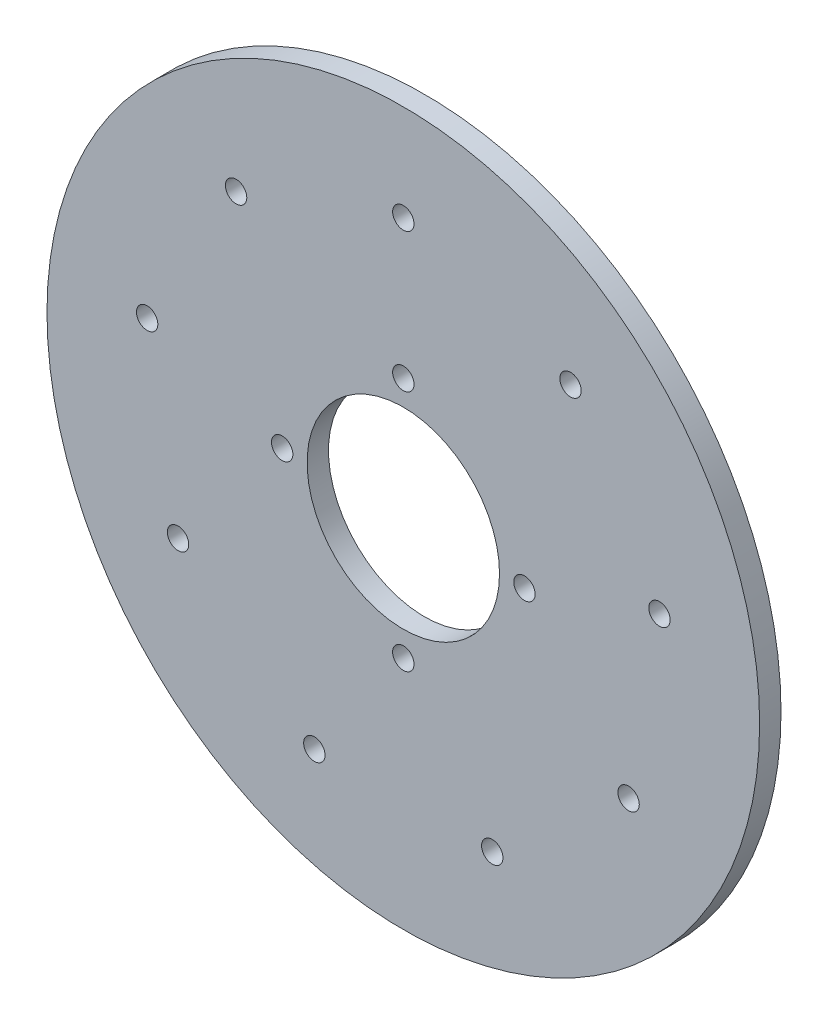
SolidWorks part; units mm, degrees
ref_plane "前视基准面" through (0, 0, 0) normal (0, 0, 1) x (1, 0, 0)
ref_plane "上视基准面" through (0, 0, 0) normal (0, 1, 0) x (1, 0, 0)
ref_plane "右视基准面" through (0, 0, 0) normal (1, 0, 0) x (0, 0, -1)
sketch "草图1" plane through (0, 0, 0) normal (0, 0, 1) x (1, 0, 0)
  line L0 (0, 0) -> (0, 17) construction
  line L1 (0, 0) -> (0, 36.5) construction
  circle A0 centre (0, 0) radius 50
  circle A1 centre (0, 17) radius 1.5
  circle A2 centre (17, 0) radius 1.5
  circle A3 centre (0, -17) radius 1.5
  circle A4 centre (-17, 0) radius 1.5
  circle A5 centre (-23.4617, 27.9606) radius 1.5
  circle A6 centre (0, 36.5) radius 1.5
  circle A7 centre (23.4617, 27.9606) radius 1.5
  circle A8 centre (35.9455, 6.3382) radius 1.5
  circle A9 centre (31.6099, -18.25) radius 1.5
  circle A10 centre (12.4837, -34.2988) radius 1.5
  circle A11 centre (-12.4837, -34.2988) radius 1.5
  circle A12 centre (-31.6099, -18.25) radius 1.5
  circle A13 centre (-35.9455, 6.3382) radius 1.5
  circle A14 centre (0, 0) radius 13.5
  point P14 (0, 0)
  point P34 (0, 0)
  dimension "D1" = 17
  dimension "D2" = 3
  dimension "D5" = 3
  dimension "D7" = 100
  dimension "D8" = 27
  dimension "D4" = 36.5
  dimension "D3" = 4
  dimension "D6" = 9
extrude "凸台-拉伸1" add sketch "草图1" along normal blind 3
